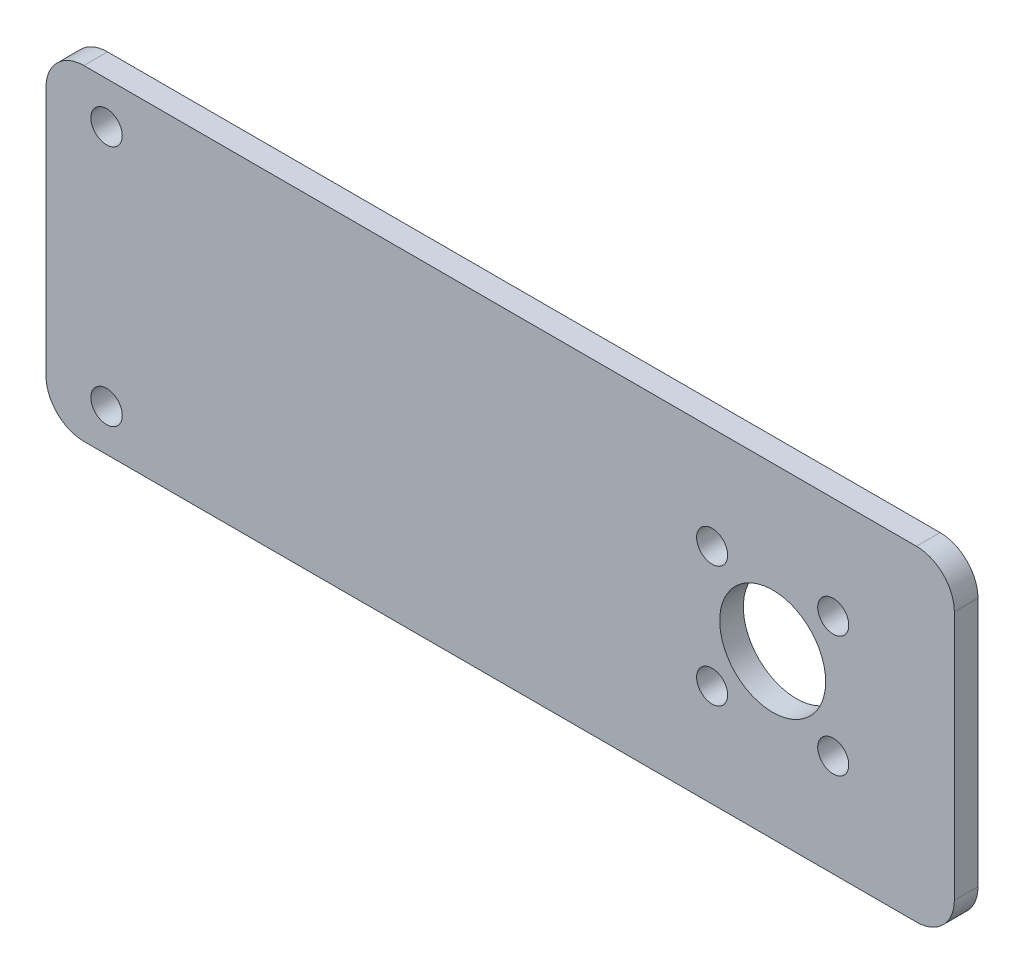
SolidWorks part; units mm, degrees
ref_plane "Front Plane" through (0, 0, 0) normal (0, 0, 1) x (1, 0, 0)
ref_plane "Top Plane" through (0, 0, 0) normal (0, 1, 0) x (1, 0, 0)
ref_plane "Right Plane" through (0, 0, 0) normal (1, 0, 0) x (0, 0, -1)
sketch "Sketch1" plane through (0, 0, 0) normal (0, 0, 1) x (1, 0, 0)
  line L1 (60, -21.5) -> (-60, -21.5)
  line L2 (60, -21.5) -> (60, 21.5)
  line L3 (60, 21.5) -> (-60, 21.5)
  line L4 (-60, -21.5) -> (-60, 21.5)
  line L5 (60, -21.5) -> (-60, 21.5) construction
  line L6 (60, 21.5) -> (-60, -21.5) construction
  line L7 (52, 16) -> (-52, 16) construction
  line L8 (52, 16) -> (52, -16) construction
  line L9 (52, -16) -> (-52, -16) construction
  line L10 (-52, 16) -> (-52, -16) construction
  line L11 (52, 16) -> (-52, -16) construction
  line L12 (52, -16) -> (-52, 16) construction
  line L13 (52, 16) -> (20, 16) construction
  line L14 (52, 16) -> (52, -16) construction
  line L15 (52, -16) -> (20, -16) construction
  line L16 (20, 16) -> (20, -16) construction
  line L17 (28, 8) -> (44, 8) construction
  line L18 (28, 8) -> (28, -8) construction
  line L19 (28, -8) -> (44, -8) construction
  line L20 (44, 8) -> (44, -8) construction
  line L21 (28, 8) -> (44, -8) construction
  line L22 (28, -8) -> (44, 8) construction
  circle A0 centre (-52, 16) radius 2.075
  circle A1 centre (-52, -16) radius 2.075
  circle A3 centre (28, 8) radius 2.05
  circle A4 centre (44, 8) radius 2.05
  circle A5 centre (44, -8) radius 2.05
  circle A6 centre (36, 0) radius 7
  circle A7 centre (28, -8) radius 2.05
  point P0 (0, 0)
  point P6 (0, 0)
  point P15 (36, 0)
  dimension "D5" = 4.15
  dimension "D11" = 14
  dimension "D12" = 4.1
  dimension "D1" = 43
  dimension "D2" = 120
  dimension "D3" = 8
  dimension "D4" = 32
  dimension "D6" = 32
  dimension "D7" = 16
  dimension "D8" = 16
  dimension "D9" = 16
  dimension "D10" = 8
extrude "Boss-Extrude1" add sketch "Sketch1" along normal blind 3.125
fillet "Fillet1" radius 5 4 edges at (60, -21.5, 1.5625) (60, 21.5, 1.5625) (-60, -21.5, 1.5625) (-60, 21.5, 1.5625)
